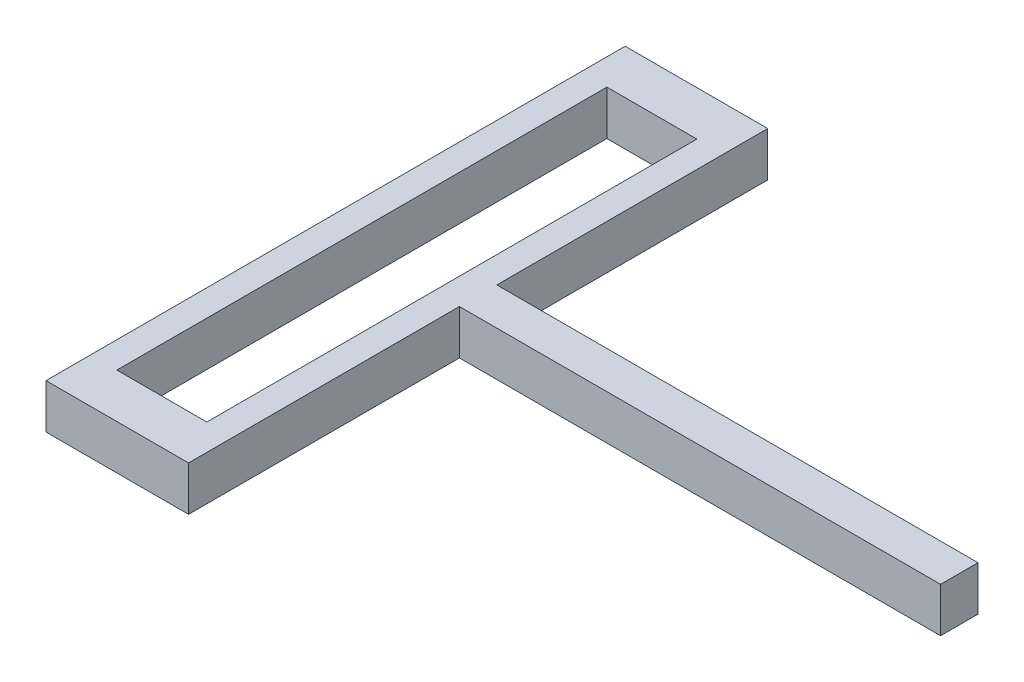
SolidWorks part; units mm, degrees
ref_plane "前基準面" through (0, 0, 0) normal (0, 0, 1) x (1, 0, 0)
ref_plane "上基準面" through (0, 0, 0) normal (0, 1, 0) x (1, 0, 0)
ref_plane "右基準面" through (0, 0, 0) normal (1, 0, 0) x (0, 0, -1)
sketch "草圖1" plane through (0, 0, 0) normal (0, 1, 0) x (1, 0, 0)
  line L0 (-29.6565, 0) -> (40.3435, 0) construction
  line L1 (-29.6565, 0) -> (-29.6565, 32.5)
  line L2 (-29.6565, 32.5) -> (-13.6565, 32.5)
  line L3 (-13.6565, 32.5) -> (-13.6565, 2.1)
  line L4 (-13.6565, 2.1) -> (40.3435, 2.1)
  line L5 (40.3435, 2.1) -> (40.3435, 0)
  line L6 (-29.6565, 0) -> (-26.7065, 0)
  line L7 (-26.7065, 0) -> (-26.7065, 27.5)
  line L8 (-26.7065, 27.5) -> (-16.6065, 27.5)
  line L9 (-16.6065, 27.5) -> (-16.6065, 0)
  line L10 (-16.6065, 0) -> (40.3435, 0)
  line L11 (-21.6565, 32.5) -> (-21.6565, 0) construction
  point P13 (0, 0)
  point P14 (-21.6565, 27.5)
  dimension "D1" = 70
  dimension "D2" = 10.1
  dimension "D3" = 5
  dimension "D4" = 16
  dimension "D5" = 27.5
  dimension "D6" = 2.1
extrude "填料-伸長1" add sketch "草圖1" along normal blind 5
mirror "鏡射1" about plane through (-16.6065, 5, 0) normal (0, 0, -1) of "填料-伸長1"
